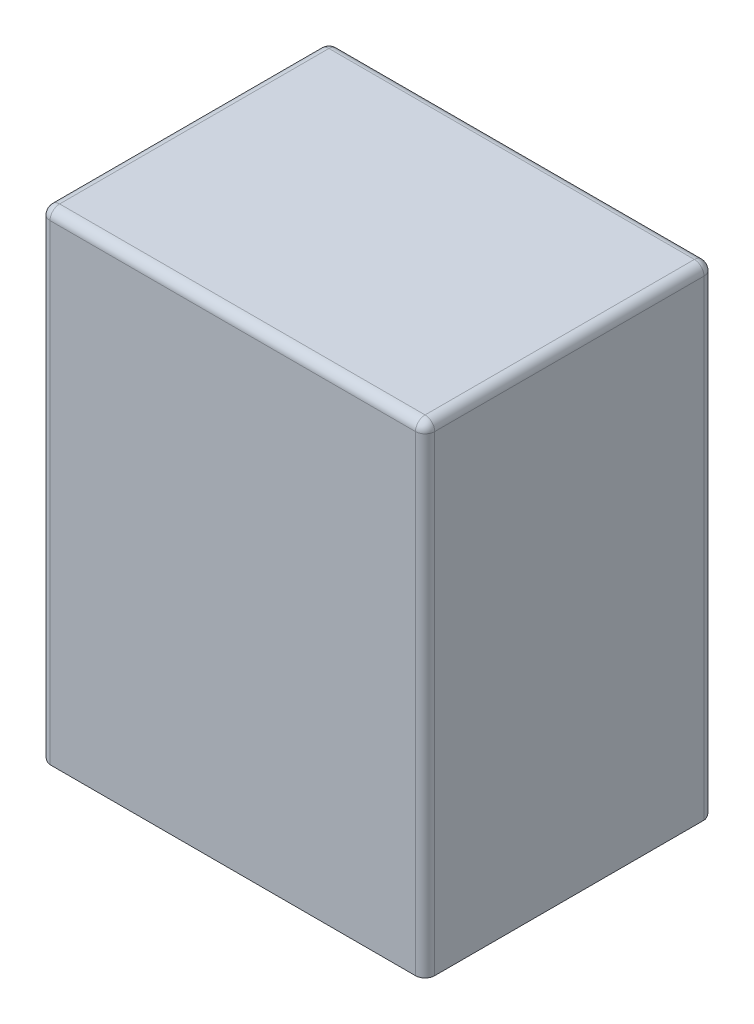
SolidWorks part; units mm, degrees
ref_plane "前视基准面" through (0, 0, 0) normal (0, 0, 1) x (1, 0, 0)
ref_plane "上视基准面" through (0, 0, 0) normal (0, 1, 0) x (1, 0, 0)
ref_plane "右视基准面" through (0, 0, 0) normal (1, 0, 0) x (0, 0, -1)
sketch "草图1" plane through (0, 0, 0) normal (0, 1, 0) x (1, 0, 0)
  line L1 (200, -150) -> (-200, -150)
  line L2 (200, -150) -> (200, 150)
  line L3 (200, 150) -> (-200, 150)
  line L4 (-200, -150) -> (-200, 150)
  line L5 (200, -150) -> (-200, 150) construction
  line L6 (200, 150) -> (-200, -150) construction
  point P0 (0, 0)
  dimension "D1" = 400
  dimension "D2" = 300
extrude "凸台-拉伸1" add sketch "草图1" along normal blind 500
fillet "圆角1" radius 10 10 edges at (-200, 250, 150) (-200, 0, 0) (200, 500, 0) (0, 500, 150) (-200, 500, 0) (200, 250, -150) (0, 500, -150) (-200, 250, -150) (0, 0, -150) (200, 250, 150)
